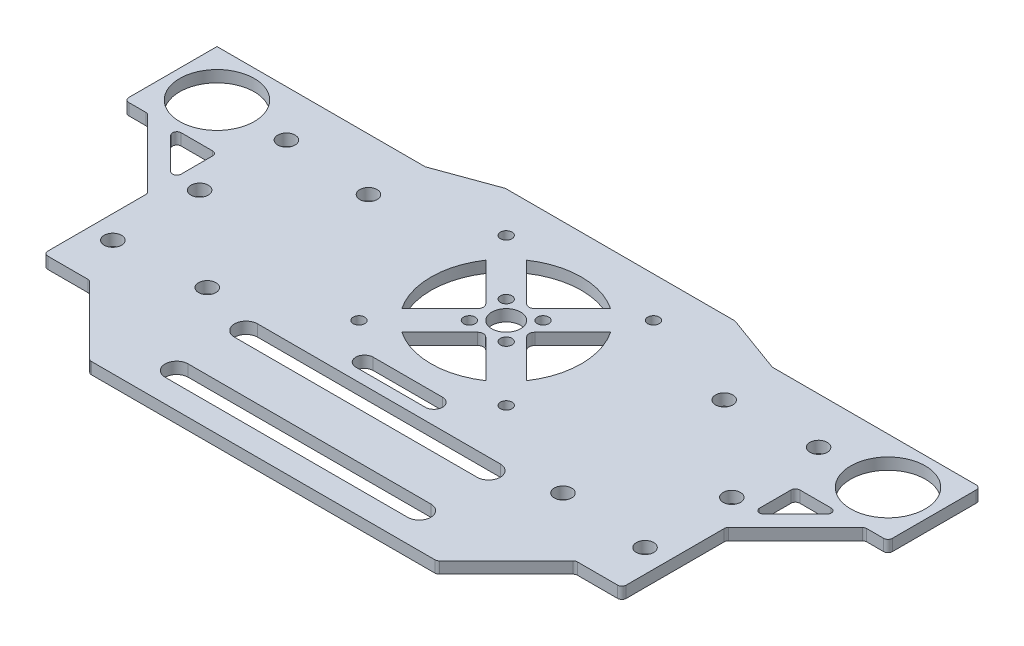
SolidWorks part; units mm, degrees
ref_plane "前视基准面" through (0, 0, 0) normal (0, 0, 1) x (1, 0, 0)
ref_plane "上视基准面" through (0, 0, 0) normal (0, 1, 0) x (1, 0, 0)
ref_plane "右视基准面" through (0, 0, 0) normal (1, 0, 0) x (0, 0, -1)
other "Configuration Table"
sketch "草图1" plane through (0, 0, 0) normal (0, 1, 0) x (1, 0, 0)
  line L0 (-50, 23) -> (50, 23)
  line L1 (50, 23) -> (50, -23)
  line L2 (50, -23) -> (-50, -23)
  line L3 (-50, -23) -> (-50, 23)
  line L5 (0, 23) -> (0, -23) construction
  line L6 (3.182, 10.182) -> (-3.182, 3.818) construction
  line L7 (7.253, 17.7886) -> (-10.7886, -0.253) construction
  line L8 (10.7886, 14.253) -> (-7.253, -3.7886) construction
  line L9 (10.7886, -0.253) -> (-7.253, 17.7886) construction
  line L10 (7.253, -3.7886) -> (-10.7886, 14.253) construction
  line L11 (-7.253, -3.7886) -> (10.7886, 14.253) construction
  line L12 (-10.7886, -0.253) -> (7.253, 17.7886) construction
  line L13 (-10.7886, 14.253) -> (7.253, -3.7886) construction
  line L14 (-7.253, 17.7886) -> (10.7886, -0.253) construction
  line L15 (10.7886, -0.253) -> (4.2426, 6.2929)
  line L16 (4.2426, 7.7071) -> (10.7886, 14.253)
  line L17 (7.253, 17.7886) -> (0.7071, 11.2426)
  line L18 (-0.7071, 11.2426) -> (-7.253, 17.7886)
  line L19 (-10.7886, 14.253) -> (-4.2426, 7.7071)
  line L20 (-4.2426, 6.2929) -> (-10.7886, -0.253)
  line L21 (-7.253, -3.7886) -> (-0.7071, 2.7574)
  line L22 (0.7071, 2.7574) -> (7.253, -3.7886)
  line L23 (-30, 23) -> (-19.848, 26.695)
  line L24 (-19.848, 26.695) -> (0.0265, 26.695)
  line L25 (30, 23) -> (19.848, 26.695)
  line L26 (19.848, 26.695) -> (-0.0265, 26.695)
  line L27 (-50, 23) -> (-66, 23)
  line L28 (-66, 23) -> (-66, 7)
  line L29 (-66, 7) -> (-50, 7)
  line L30 (-50, 7) -> (-50, 23)
  line L31 (-58, 7) -> (-50, -1)
  line L32 (-62, 7) -> (-50, -5)
  line L33 (-50, -1) -> (-50, -5)
  line L34 (-58, 7) -> (-62, 7)
  line L35 (58, 7) -> (62, 7)
  line L36 (50, -1) -> (50, -5)
  line L37 (62, 7) -> (50, -5)
  line L38 (58, 7) -> (50, -1)
  line L39 (50, 7) -> (50, 23)
  line L40 (66, 7) -> (50, 7)
  line L41 (66, 23) -> (66, 7)
  line L42 (50, 23) -> (66, 23)
  line L43 (-42, -23) -> (-30, -35)
  line L44 (-30, -35) -> (30, -35)
  line L45 (42, -23) -> (30, -35)
  line L46 (-42, -23) -> (42, -23)
  line L47 (-46, 23) -> (-46, -23) construction
  line L48 (-50, 0) -> (50, 0) construction
  line L49 (-6, -11.5) -> (6, -11.5) construction
  line L50 (-6, -10) -> (6, -10)
  line L51 (-20.9696, -17) -> (20.9696, -17) construction
  line L52 (-20.9696, -15) -> (20.9696, -15)
  line L53 (-20.9696, -19) -> (20.9696, -19)
  line L54 (-20.9696, -29) -> (20.9696, -29) construction
  line L55 (-20.9696, -27) -> (20.9696, -27)
  line L56 (-20.9696, -31) -> (20.9696, -31)
  line L57 (-6, -13) -> (6, -13)
  circle A0 centre (0, 7) radius 2.5
  circle A1 centre (3.182, 10.182) radius 1
  circle A2 centre (3.182, 3.818) radius 1
  circle A3 centre (-3.182, 3.818) radius 1
  circle A4 centre (-3.182, 10.182) radius 1
  circle A5 centre (0, 7) radius 13
  circle A6 centre (12.7279, 19.7279) radius 1
  circle A7 centre (12.7279, -5.7279) radius 1
  circle A8 centre (-12.7279, -5.7279) radius 1
  circle A9 centre (-12.7279, 19.7279) radius 1
  arc A10 (-0.7071, 2.7574) -> (0.7071, 2.7574) centre (0, 2.0503) cw
  arc A11 (-4.2426, 7.7071) -> (-4.2426, 6.2929) centre (-4.9497, 7) cw
  arc A12 (0.7071, 11.2426) -> (-0.7071, 11.2426) centre (0, 11.9497) cw
  arc A13 (4.2426, 6.2929) -> (4.2426, 7.7071) centre (4.9497, 7) cw
  circle A15 centre (-58, 15) radius 6.45
  circle A16 centre (58, 15) radius 6.45
  circle A17 centre (-46, 15) radius 1.5
  circle A18 centre (-46, 0) radius 1.5
  circle A19 centre (-46, -15) radius 1.5
  circle A20 centre (46, -15) radius 1.5
  circle A21 centre (46, 0) radius 1.5
  circle A22 centre (46, 15) radius 1.5
  circle A23 centre (30.7465, 13.935) radius 1.5
  circle A24 centre (30.7465, -13.935) radius 1.5
  circle A25 centre (-30.7465, -13.935) radius 1.5
  circle A26 centre (-30.7465, 13.935) radius 1.5
  circle A27 centre (0, 7) radius 15
  arc A29 (-20.9696, -15) -> (-20.9696, -19) centre (-20.9696, -17) ccw
  arc A30 (20.9696, -19) -> (20.9696, -15) centre (20.9696, -17) ccw
  arc A31 (-20.9696, -27) -> (-20.9696, -31) centre (-20.9696, -29) ccw
  arc A32 (20.9696, -31) -> (20.9696, -27) centre (20.9696, -29) ccw
  arc A33 (-6, -10) -> (-6, -13) centre (-6, -11.5) ccw
  arc A34 (6, -13) -> (6, -10) centre (6, -11.5) ccw
  point P5 (50, 0)
  point P6 (0, 23)
  point P42 (0, 3.4645)
  point P45 (-3.5355, 7)
  point P48 (0, 10.5355)
  point P51 (3.5355, 7)
  point P64 (-58, 23)
  point P66 (-66, 15)
  point P84 (0, -35)
  point P92 (-50, 0)
  point P111 (0, -11.5)
  point P116 (0, -17)
  point P122 (0, -29)
  point P132 (3.0415, -13.3371)
  dimension "D3" = 5
  dimension "D4" = 2
  dimension "D8" = 26
  dimension "D9" = 2
  dimension "D13" = 1
  dimension "D18" = 16
  dimension "D19" = 16
  dimension "D20" = 12.9
  dimension "D26" = 3
  dimension "D27" = 4
  dimension "D28" = 3
  dimension "D29" = 3
  dimension "D32" = 3
  dimension "D35" = 30
  dimension "D36" = 1.5
  dimension "D1" = 100
  dimension "D2" = 46
  dimension "D6" = 9
  dimension "D7" = 45
  dimension "D11" = 18
  dimension "D14" = 16
  dimension "D15" = 20
  dimension "D16" = 20
  dimension "D17" = 3.695
  dimension "D21" = 4
  dimension "D22" = 45
  dimension "D23" = 8
  dimension "D24" = 45
  dimension "D25" = 12
  dimension "D30" = 15
  dimension "D31" = 15
  dimension "D33" = 61.493
  dimension "D34" = 27.87
  dimension "D37" = 6
  dimension "D38" = 12
  dimension "D39" = 6
  dimension "D40" = 2
  dimension "D41" = 2
  dimension "D42" = 20.9696
  dimension "D43" = 5.5
  dimension "D5" = 4
  dimension "D10" = 4
  dimension "D12" = 4
extrude "凸台-拉伸1" add sketch "草图1" along normal blind 2
fillet "圆角1" radius 0.75 19 edges at (66, 1, -23) (66, 1, -7) (62, 1, -7) (50, 1, 5) (50, 1, 23) (42, 1, 23) (30, 1, 35) (-30, 1, 35) (-42, 1, 23) (-50, 1, 23) (-50, 1, 5) (-62, 1, -7) (-66, 1, -7) (50, 1, -7) (50, 1, 1) (58, 1, -7) (-50, 1, 1) (-50, 1, -7) (-58, 1, -7)
sketch "草图2" plane through (0, 2, 0) normal (0, 1, 0) x (1, 0, 0)
  text T0 "M3" font "@Microsoft YaHei UI" height 2
  text T1 "M2" font "@Microsoft YaHei UI" height 2
  text T2 "M3" font "@Microsoft YaHei UI" height 2
